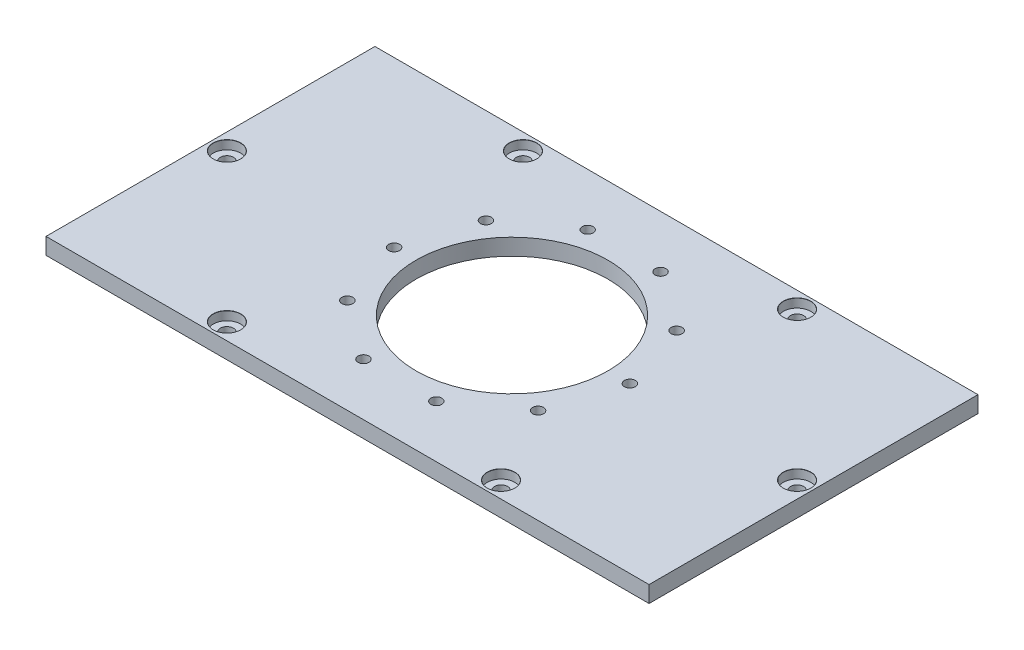
SolidWorks part; units mm, degrees
ref_plane "Ebene vorne" through (0, 0, 0) normal (0, 0, 1) x (1, 0, 0)
ref_plane "Ebene oben" through (0, 0, 0) normal (0, 1, 0) x (1, 0, 0)
ref_plane "Ebene rechts" through (0, 0, 0) normal (1, 0, 0) x (0, 0, -1)
sketch "Skizze1" plane through (0, 0, 0) normal (0, 1, 0) x (1, 0, 0)
  line L1 (0, 0) -> (110, 0)
  line L2 (0, 0) -> (0, 60)
  line L3 (0, 60) -> (110, 60)
  line L4 (110, 0) -> (110, 60)
  dimension "D1" = 60
  dimension "D2" = 110
extrude "Aufsatz-Linear austragen1" add sketch "Skizze1" along normal blind 3
hole_wizard "Ø2.4 (2.4) Durchmesser Bohrung1" positions "Skizze2" profile "Skizze3" hole size "Ø2.4" standard "DIN"
sketch "Skizze2" plane through (0, 3, 0) normal (0, 1, 0) x (1, 0, 0)
  line L0 (110, 60) -> (0, 60) construction
  line L1 (110, 0) -> (110, 60) construction
  line L2 (0, -1.65) -> (0, 1.65) construction
  line L3 (-1.65, 0) -> (1.65, 0) construction
  point P0 (30, 57)
  point P2 (80, 57)
  point P4 (107, 30)
  point P6 (80, 3)
  point P8 (30, 3)
  point P10 (3, 30)
  point P21 (133.0887, 32.8034)
  dimension "D1" = 3
  dimension "D2" = 3
  dimension "D3" = 3
  dimension "D4" = 3
  dimension "D5" = 3
  dimension "D6" = 3
  dimension "D7" = 30
  dimension "D8" = 30
  dimension "D9" = 30
  dimension "D10" = 30
  dimension "D11" = 30
  dimension "D12" = 30
sketch "Skizze3" plane through (30, 3, -57) normal (1, 0, 0) x (0, 0, 1)
  line L0 (0, 0) -> (0, 10.721)
  line L1 (0, 10.721) -> (1.2, 10)
  line L2 (1.2, 10) -> (1.2, 0.025)
  line L3 (1.2, 0.025) -> (1.225, 0)
  line L5 (1.225, 0) -> (0, 0)
  line L6 (-1.2, 0.025) -> (-1.225, 0) construction
  line L10 (0, 10.721) -> (-1.2, 10) construction
  line L11 (0, -6.35) -> (0, 107.95) construction
  dimension "Bohrerdurchmesser" = 2.4
  dimension "Bohrungstiefe" = 10
  dimension "Senkdurchmesser2 (Oben)" = 2.45
  dimension "Senkwinkel2 (Oben)" = 90
  dimension "Spitzenwinkel" = 118
hole_wizard "Stirnsenkung für M2 Flachkopfschraube mit Schlitz1" positions "Skizze6" profile "Skizze7" counterbore size "M2" standard "DIN"
sketch "Skizze6" plane through (0, 3, 0) normal (0, 1, 0) x (1, 0, 0)
  point P0 (80, 3)
  point P3 (107, 30)
  point P6 (80, 57)
  point P9 (30, 57)
  point P12 (3, 30)
  point P15 (30, 3)
sketch "Skizze7" plane through (80, 3, -3) normal (1, 0, 0) x (0, 0, 1)
  line L0 (0, 0) -> (0, 2.721)
  line L1 (0, 2.721) -> (1.2, 2)
  line L2 (1.2, 2) -> (1.2, 1.6)
  line L3 (1.2, 1.6) -> (2.5, 1.6)
  line L5 (2.5, 1.6) -> (2.5, 0.025)
  line L6 (2.5, 0.025) -> (2.525, 0)
  line L7 (2.525, 0) -> (0, 0)
  line L8 (-2.5, 0.025) -> (-2.525, 0) construction
  line L10 (0, 2.721) -> (-1.2, 2) construction
  line L11 (0, -6.35) -> (0, 107.95) construction
  dimension "Bohrerdurchmesser" = 2.4
  dimension "Bohrungstiefe" = 2
  dimension "Senkdurchmesser2" = 5
  dimension "Senktiefe2" = 1.6
  dimension "Senkdurchmesser4 (Oben)" = 5.05
  dimension "Senkwinkel2 (Oben)" = 90
  dimension "Spitzenwinkel" = 118
sketch "Skizze8" plane through (0, 3, 0) normal (0, 1, 0) x (1, 0, 0)
  line L0 (55, -24.4296) -> (55, 94.5281) construction
  line L1 (110, 0) -> (110, 60) construction
  line L3 (0, 60) -> (0, 0) construction
  line L4 (147.1504, 30) -> (-23.042, 30) construction
  line L5 (0, 0) -> (110, 0) construction
  line L6 (110, 60) -> (0, 60) construction
  circle A1 centre (37.6061, 42.6374) radius 1
  circle A2 centre (48.3561, 50.4477) radius 1
  circle A3 centre (61.6439, 50.4477) radius 1
  circle A4 centre (72.3939, 42.6374) radius 1
  circle A5 centre (76.5, 30) radius 1
  circle A6 centre (72.3939, 17.3626) radius 1
  circle A7 centre (61.6439, 9.5523) radius 1
  circle A8 centre (48.3561, 9.5523) radius 1
  circle A9 centre (37.6061, 17.3626) radius 1
  circle A10 centre (33.5, 30) radius 1
  circle A17 centre (55, 30) radius 17.5
  point P14 (55, 30)
  dimension "D1" = 2
  dimension "D3" = 43
  dimension "D11" = 35
  dimension "D2" = 10
extrude "Schnitt-Linear austragen1" cut sketch "Skizze8" against normal up to surface (3 mm away) up to face at (30, 0, -58.2)
